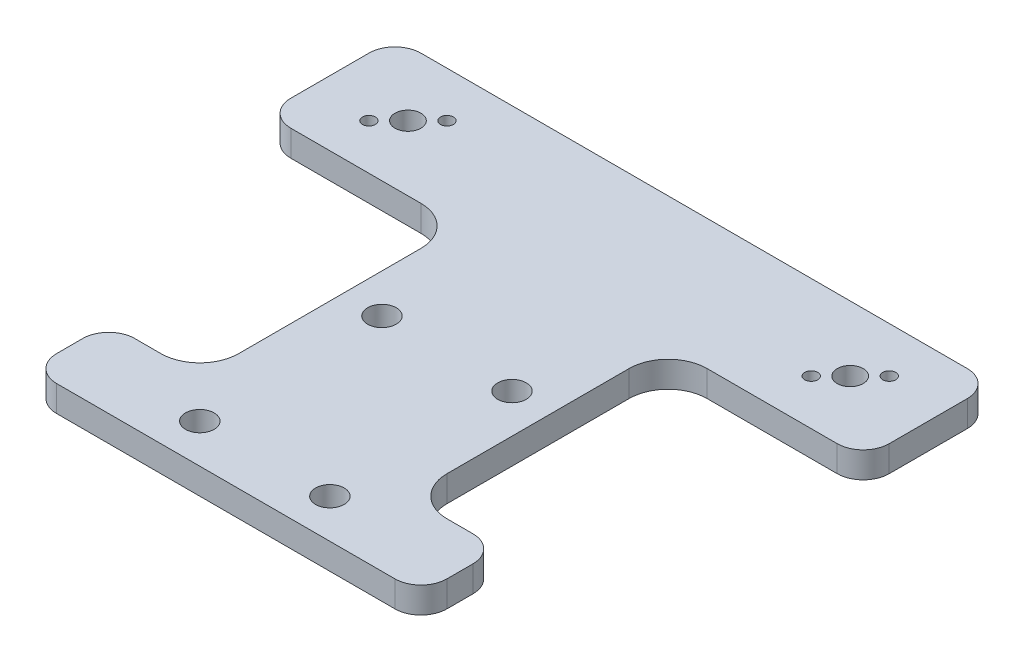
SolidWorks part; units mm, degrees
ref_plane "Vorne" through (0, 0, 0) normal (0, 0, 1) x (1, 0, 0)
ref_plane "Oben" through (0, 0, 0) normal (0, 1, 0) x (1, 0, 0)
ref_plane "Rechts" through (0, 0, 0) normal (1, 0, 0) x (0, 0, -1)
ref_plane "E_Boden" through (0, 1, 0) normal (0, 1, 0) x (1, 0, 0)
sketch "Skizze1" plane through (0, 0, 0) normal (0, 1, 0) x (1, 0, 0)
  line L0 (0, -84.2382) -> (0, 127.1868) construction
  line L1 (-165.4867, 0) -> (188.3198, 0) construction
  line L2 (-105, 90) -> (105, 90)
  line L3 (-115, 80) -> (-115, 50)
  line L8 (-105, 40) -> (-55, 40)
  line L9 (-40, 25) -> (-40, -45)
  line L10 (-55, -60) -> (-65, -60)
  line L11 (-75, -70) -> (-75, -80)
  line L12 (-65, -90) -> (65, -90)
  line L13 (75, -70) -> (75, -80)
  line L14 (55, -60) -> (65, -60)
  line L15 (40, 25) -> (40, -45)
  line L16 (105, 40) -> (55, 40)
  line L17 (115, 80) -> (115, 50)
  arc A0 (40, 25) -> (55, 40) centre (55, 25) cw
  arc A1 (55, -60) -> (40, -45) centre (55, -45) cw
  arc A2 (-40, -45) -> (-55, -60) centre (-55, -45) cw
  arc A3 (-55, 40) -> (-40, 25) centre (-55, 25) cw
  arc A4 (75, -70) -> (65, -60) centre (65, -70) ccw
  arc A5 (75, -80) -> (65, -90) centre (65, -80) cw
  arc A6 (-75, -80) -> (-65, -90) centre (-65, -80) ccw
  arc A7 (-65, -60) -> (-75, -70) centre (-65, -70) ccw
  arc A8 (-115, 50) -> (-105, 40) centre (-105, 50) ccw
  arc A9 (105, 40) -> (115, 50) centre (105, 50) ccw
  arc A10 (115, 80) -> (105, 90) centre (105, 80) ccw
  arc A11 (-105, 90) -> (-115, 80) centre (-105, 80) ccw
  point P15 (0, -90)
  point P16 (0, 90)
  point P22 (40, 40)
  point P25 (40, -60)
  point P28 (-40, -60)
  point P31 (-40, 40)
  point P34 (75, -60)
  point P37 (75, -90)
  point P40 (-75, -90)
  point P43 (-75, -60)
  point P46 (-115, 40)
  point P49 (115, 40)
  point P52 (115, 90)
  point P55 (-115, 90)
  dimension "D7" = 15
  dimension "D8" = 10
  dimension "D1" = 230
  dimension "D2" = 50
  dimension "D3" = 130
  dimension "D4" = 150
  dimension "D5" = 80
  dimension "D6" = 30
extrude "Aufsatz-Linear austragen1" add sketch "Skizze1" along normal blind 10
hole_wizard "Ø10.0 (10) Durchmesser Bohrung1" positions "Skizze6" profile "Skizze7" hole size "Ø10.0" standard "DIN" end condition through all
sketch "Skizze6" plane through (0, 10, 0) normal (0, 1, 0) x (1, 0, 0)
  line L2 (105, 90) -> (-105, 90) construction
  line L3 (0, 90) -> (0, -90) construction
  line L4 (-65, -90) -> (65, -90) construction
  point P0 (-85, 65)
  point P2 (85, 65)
  dimension "D1" = 25
  dimension "D2" = 25
  dimension "D3" = 170
sketch "Skizze7" plane through (-85, 10, -65) normal (1, 0, 0) x (0, 0, 1)
  line L0 (0, 0) -> (0, 10)
  line L1 (0, 10) -> (5, 10)
  line L2 (5, 10) -> (5, 0)
  line L5 (5, 0) -> (0, 0)
  line L11 (0, -6.35) -> (0, 107.95) construction
  dimension "Bohrerdurchmesser" = 10
  dimension "Bohrungstiefe" = 10
hole_wizard "Ø5.0 (5) Durchmesser Bohrung1" positions "Skizze11" profile "Skizze12" hole size "Ø5.0" standard "DIN" end condition through all
sketch "Skizze11" plane through (0, 0, 0) normal (0, -1, 0) x (-1, 0, 0)
  line L0 (77.5, 72.5) -> (77.5, 45.1453) construction
  line L3 (92.5, 57.5) -> (92.5, 79.091) construction
  line L6 (-92.5, 72.5) -> (-92.5, 57.5) construction
  line L9 (-77.5, 57.5) -> (-77.5, 72.5) construction
  line L12 (-77.5, 57.5) -> (-92.5, 57.5) construction
  line L15 (-77.5, 72.5) -> (-92.5, 72.5) construction
  line L18 (77.5, 72.5) -> (92.5, 72.5) construction
  line L21 (92.5, 57.5) -> (77.5, 57.5) construction
  line L24 (80, 65) -> (71.5087, 65) construction
  line L25 (71.5087, 65) -> (96.6058, 65) construction
  line L28 (85, 60) -> (85, 53.6887) construction
  line L29 (85, 53.6887) -> (85, 75.0654) construction
  line L30 (-90, 65) -> (-74.1442, 65) construction
  line L32 (-85, 70) -> (-85, 55.7381) construction
  circle A0 centre (85, 65) radius 5 construction
  circle A1 centre (-85, 65) radius 5 construction
  point P0 (77.5, 72.5)
  point P2 (92.5, 57.5)
  point P4 (-92.5, 72.5)
  point P6 (-77.5, 57.5)
  point P43 (85, 72.5)
  dimension "D1" = 15
  dimension "D2" = 15
  dimension "D3" = 7.5
  dimension "D4" = 7.5
  dimension "D5" = 15
  dimension "D6" = 15
  dimension "D7" = 7.5
  dimension "D8" = 7.5
sketch "Skizze12" plane through (-77.5, 0, -72.5) normal (1, 0, 0) x (0, 0, -1)
  line L0 (0, 0) -> (0, 10)
  line L1 (0, 10) -> (2.5, 10)
  line L2 (2.5, 10) -> (2.5, 0)
  line L5 (2.5, 0) -> (0, 0)
  line L11 (0, -6.35) -> (0, 107.95) construction
  dimension "Bohrerdurchmesser" = 5
  dimension "Bohrungstiefe" = 10
hole_wizard "Durchgangsloch für M101" positions "Skizze13" profile "Skizze14" hole size "M10" standard "DIN" end condition through all
sketch "Skizze13" plane through (0, 0, 0) normal (0, -1, 0) x (-1, 0, 0)
  line L0 (0, 90) -> (0, -90) construction
  line L1 (-105, 90) -> (105, 90) construction
  line L2 (65, -90) -> (-65, -90) construction
  line L4 (-40, -45) -> (-40, 25) construction
  line L5 (40, 25) -> (40, -45) construction
  point P0 (-25, -5)
  point P2 (-25, -75)
  point P4 (25, -5)
  point P6 (25, -75)
  dimension "D1" = 70
  dimension "D2" = 70
  dimension "D3" = 15
  dimension "D4" = 15
  dimension "D5" = 15
  dimension "D6" = 15
sketch "Skizze14" plane through (25, 0, 5) normal (1, 0, 0) x (0, 0, -1)
  line L0 (0, 0) -> (0, 10)
  line L1 (0, 10) -> (5.5, 10)
  line L2 (5.5, 10) -> (5.5, 0)
  line L5 (5.5, 0) -> (0, 0)
  line L11 (0, -6.35) -> (0, 107.95) construction
  dimension "Bohrerdurchmesser" = 11
  dimension "Bohrungstiefe" = 10
